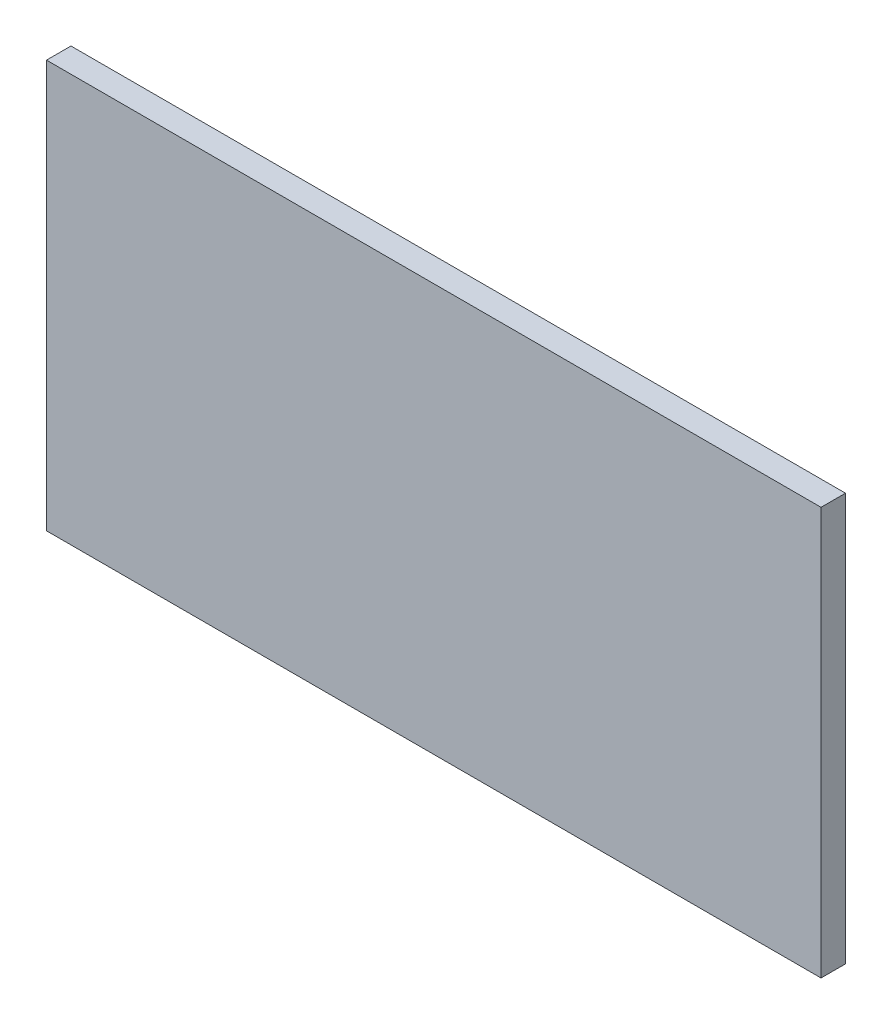
SolidWorks part; units mm, degrees
ref_plane "前视基准面" through (0, 0, 0) normal (0, 0, 1) x (1, 0, 0)
ref_plane "上视基准面" through (0, 0, 0) normal (0, 1, 0) x (1, 0, 0)
ref_plane "右视基准面" through (0, 0, 0) normal (1, 0, 0) x (0, 0, -1)
sketch "草图1" plane through (0, 0, 0) normal (0, 0, 1) x (1, 0, 0)
  line L1 (0, 0) -> (380, 0)
  line L2 (0, 0) -> (0, 200)
  line L3 (0, 200) -> (380, 200)
  line L4 (380, 0) -> (380, 200)
  dimension "D1" = 380
  dimension "D2" = 200
extrude "凸台-拉伸1" add sketch "草图1" along normal blind 12
